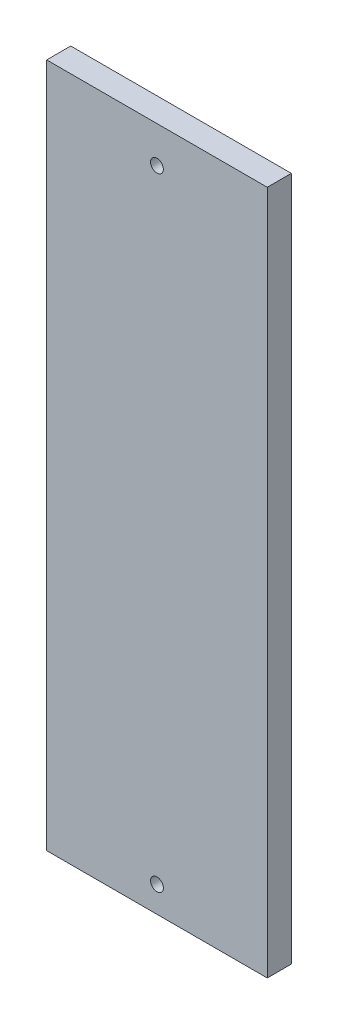
SolidWorks part; units mm, degrees
ref_plane "Front Plane" through (0, 0, 0) normal (0, 0, 1) x (1, 0, 0)
ref_plane "Top Plane" through (0, 0, 0) normal (0, 1, 0) x (1, 0, 0)
ref_plane "Right Plane" through (0, 0, 0) normal (1, 0, 0) x (0, 0, -1)
sketch "Sketch1" plane through (0, 0, 0) normal (0, 0, 1) x (1, 0, 0)
  line L1 (0, 0) -> (55, 0)
  line L2 (0, 0) -> (0, 164.75)
  line L3 (0, 164.75) -> (55, 164.75)
  line L4 (55, 0) -> (55, 164.75)
  dimension "D1" = 164.75
  dimension "D2" = 55
extrude "Boss-Extrude1" add sketch "Sketch1" along normal blind 6
hole_wizard "M3 Clearance Slot1" positions "Sketch2" profile "Sketch3" size "M3" standard "ANSI Metric" slot yes end condition through all
sketch "Sketch2" plane through (0, 0, 0) normal (0, 0, -1) x (-1, 0, 0)
  line L0 (-55, 164.75) -> (0, 164.75) construction
  line L1 (0, 164.75) -> (0, 0) construction
  line L2 (-55, 0) -> (-55, 164.75) construction
  line L3 (0, 0) -> (-55, 0) construction
  point P0 (-27.5, 161.67)
  point P2 (-27.5, 6.48)
  dimension "D1" = 3.08
  dimension "D2" = 27.5
  dimension "D3" = 27.5
  dimension "D4" = 6.48
sketch "Sketch3" plane through (27.5, 161.67, 0) normal (1, 0, 0) x (0, 1, 0)
  line L0 (0, 0) -> (0, 6)
  line L1 (0, 6) -> (1.6, 6)
  line L2 (1.6, 6) -> (1.6, 0)
  line L5 (1.6, 0) -> (0, 0)
  line L11 (0, -6.35) -> (0, 107.95) construction
  dimension "Thru Hole Dia." = 3.2
  dimension "Thru Hole Depth" = 6
sketch "Sketch4" plane through (0, 164.75, 0) normal (0, 1, 0) x (1, 0, 0)
  line L1 (55, 0) -> (0, 0)
  line L2 (55, 0) -> (55, -6)
  line L3 (55, -6) -> (0, -6)
  line L4 (0, 0) -> (0, -6)
extrude "Boss-Extrude2" add sketch "Sketch4" along normal blind 6
